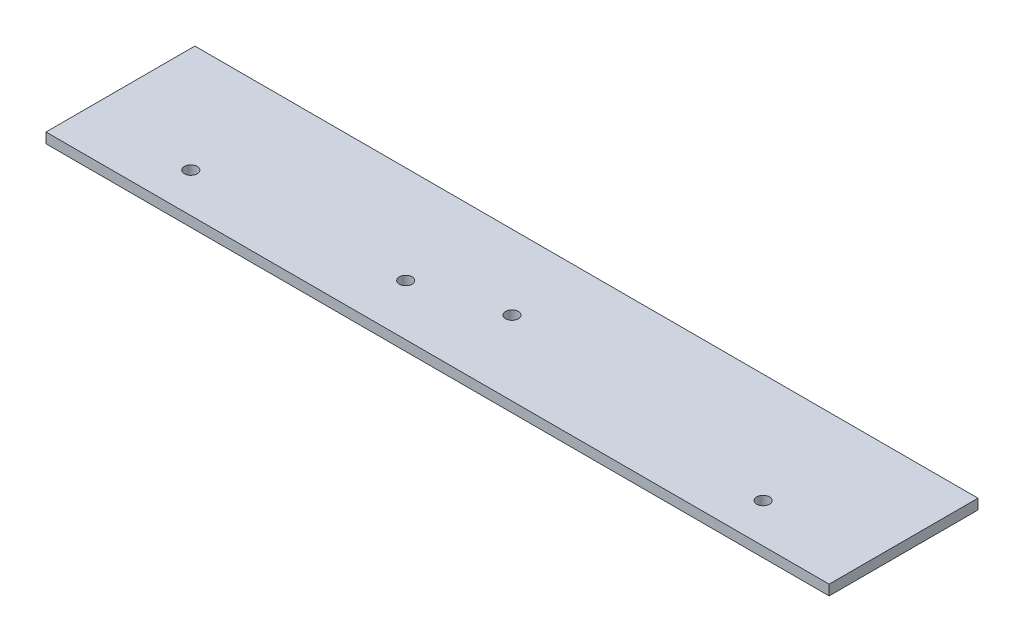
SolidWorks part; units mm, degrees
ref_plane "Front Plane" through (0, 0, 0) normal (0, 0, 1) x (1, 0, 0)
ref_plane "Top Plane" through (0, 0, 0) normal (0, 1, 0) x (1, 0, 0)
ref_plane "Right Plane" through (0, 0, 0) normal (1, 0, 0) x (0, 0, -1)
sketch "Sketch1" plane through (0, 0, 0) normal (0, 1, 0) x (1, 0, 0)
  line L0 (-71, -8.695) -> (71, -8.695) construction
  line L2 (-97.1504, -18.4656) -> (97.1504, -18.4656)
  line L3 (-97.1504, -18.4656) -> (-97.1504, 18.4656)
  line L4 (-97.1504, 18.4656) -> (97.1504, 18.4656)
  line L5 (97.1504, -18.4656) -> (97.1504, 18.4656)
  line L6 (-97.1504, -18.4656) -> (97.1504, 18.4656) construction
  line L7 (-97.1504, 18.4656) -> (97.1504, -18.4656) construction
  circle A0 centre (-71, -8.695) radius 1.5875
  circle A1 centre (71, -8.695) radius 1.5875
  circle A2 centre (0, 0) radius 1.5875
  circle A3 centre (-20.62, -5.75) radius 1.5875
  point P6 (0, 0)
  dimension "D2" = 3.175
  dimension "D1" = 142
  dimension "D3" = 20.62
  dimension "D4" = 5.75
  dimension "D5" = 8.695
extrude "Boss-Extrude1" add sketch "Sketch1" along normal mid plane 2.54
sketch "Sketch2" plane through (0, -1.27, 0) normal (0, -1, 0) x (-1, 0, 0)
  line L0 (20.62, -5.75) -> (26.2458, -5.75) construction
